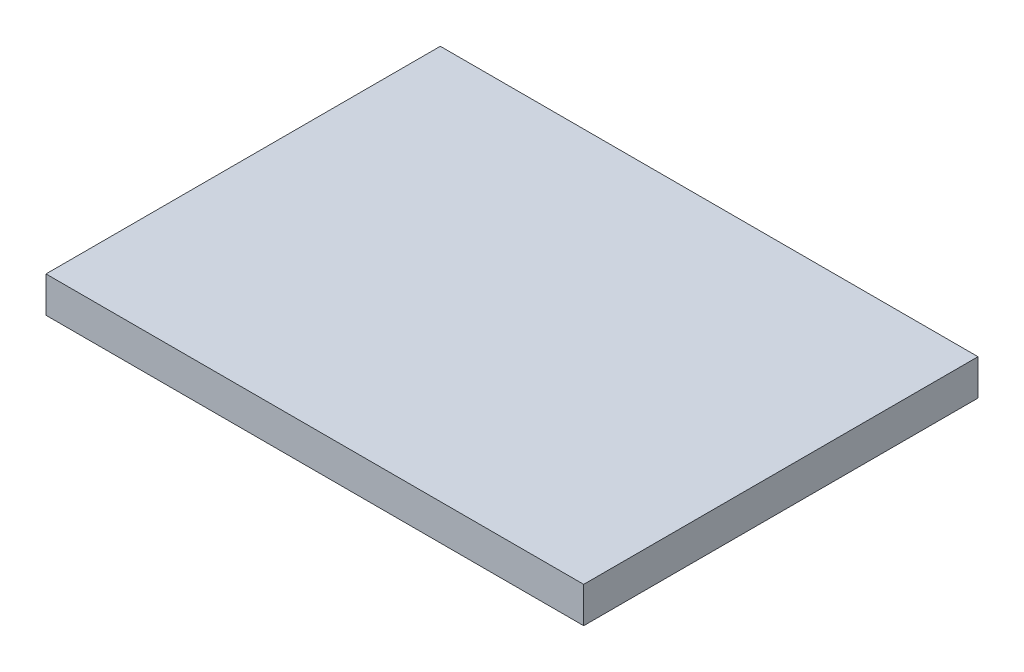
SolidWorks part; units mm, degrees
ref_plane "Front Plane" through (0, 0, 0) normal (0, 0, 1) x (1, 0, 0)
ref_plane "Top Plane" through (0, 0, 0) normal (0, 1, 0) x (1, 0, 0)
ref_plane "Right Plane" through (0, 0, 0) normal (1, 0, 0) x (0, 0, -1)
sketch "Sketch1" plane through (0, 0, 0) normal (0, 1, 0) x (1, 0, 0)
  line L1 (-7.5, -5.5) -> (7.5, -5.5)
  line L2 (-7.5, -5.5) -> (-7.5, 5.5)
  line L3 (-7.5, 5.5) -> (7.5, 5.5)
  line L4 (7.5, -5.5) -> (7.5, 5.5)
  line L5 (-7.5, -5.5) -> (7.5, 5.5) construction
  line L6 (-7.5, 5.5) -> (7.5, -5.5) construction
  point P0 (0, 0)
  dimension "D1" = 15
  dimension "D2" = 11
extrude "Boss-Extrude1" add sketch "Sketch1" along normal blind 1
